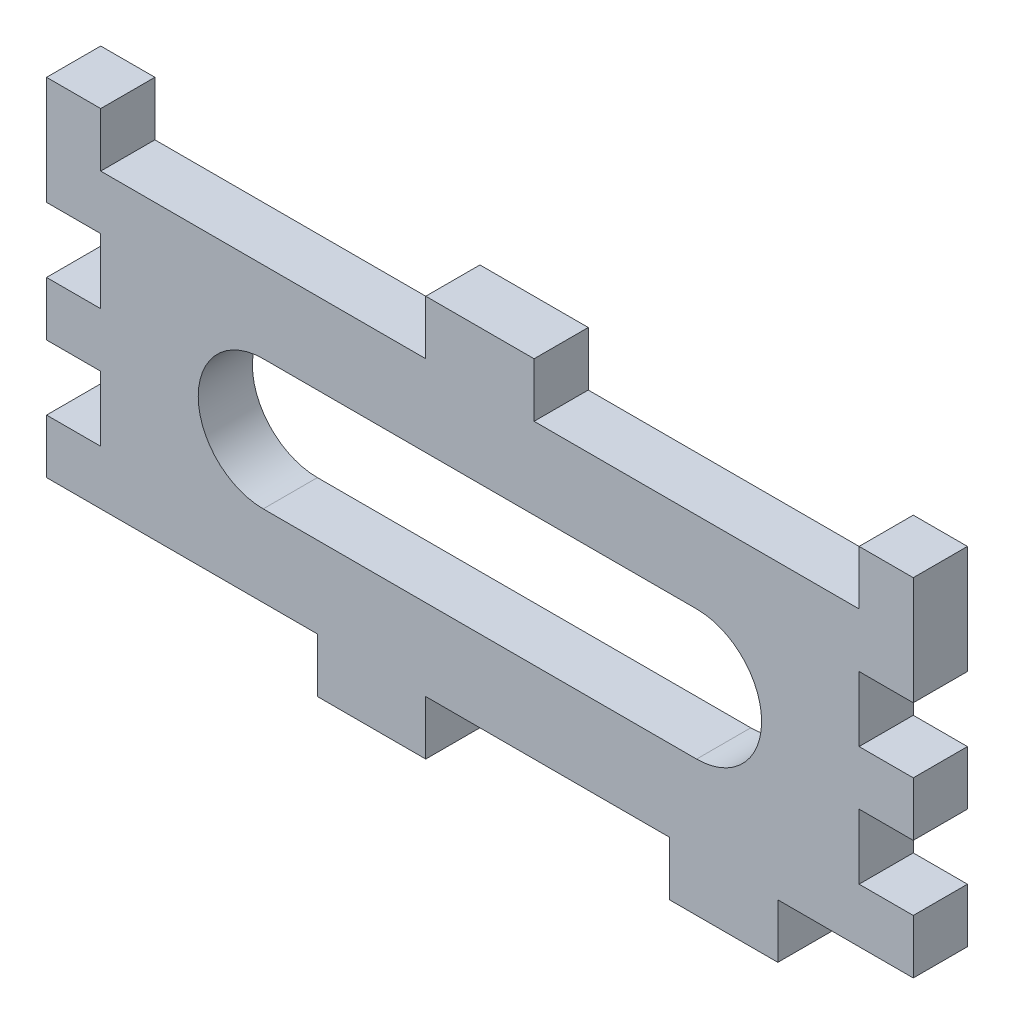
SolidWorks part; units mm, degrees
material "Balsa"
ref_plane "Plan de face" through (0, 0, 0) normal (0, 0, 1) x (1, 0, 0)
ref_plane "Plan de dessus" through (0, 0, 0) normal (0, 1, 0) x (1, 0, 0)
ref_plane "Plan de droite" through (0, 0, 0) normal (1, 0, 0) x (0, 0, -1)
sketch "Esquisse1" plane through (0, 0, 0) normal (0, 0, 1) x (1, 0, 0)
  line L1 (-138.9836, 170.4211) -> (-58.9836, 170.4211)
  line L2 (-138.9836, 170.4211) -> (-138.9836, 143.4211)
  line L3 (-138.9836, 143.4211) -> (-58.9836, 143.4211)
  line L4 (-58.9836, 170.4211) -> (-58.9836, 143.4211)
extrude "Boss.-Extru.1" add sketch "Esquisse1" against normal blind 5
sketch "Esquisse2" plane through (0, 0, 0) normal (0, 0, 1) x (1, 0, 0)
  line L0 (-98.9836, 223.4211) -> (-98.9836, 138.4211) construction
  line L1 (-118.9836, 156.9211) -> (-78.9836, 156.9211) construction
  line L2 (-118.9836, 162.9211) -> (-78.9836, 162.9211)
  line L3 (-118.9836, 150.9211) -> (-78.9836, 150.9211)
  line L4 (-138.9836, 143.4211) -> (-58.9836, 143.4211) construction
  line L5 (-58.9836, 143.4211) -> (-58.9836, 170.4211) construction
  line L6 (-63.9836, 165.4211) -> (-58.9836, 165.4211)
  line L7 (-63.9836, 165.4211) -> (-63.9836, 159.4211)
  line L8 (-63.9836, 159.4211) -> (-58.9836, 159.4211)
  line L9 (-58.9836, 165.4211) -> (-58.9836, 159.4211)
  line L10 (-138.9836, 143.4211) -> (-58.9836, 143.4211) construction
  line L11 (-63.9836, 154.4211) -> (-58.9836, 154.4211)
  line L12 (-63.9836, 154.4211) -> (-63.9836, 148.4211)
  line L13 (-63.9836, 148.4211) -> (-58.9836, 148.4211)
  line L14 (-58.9836, 154.4211) -> (-58.9836, 148.4211)
  line L15 (-58.9836, 170.4211) -> (-138.9836, 170.4211) construction
  line L16 (-138.9836, 154.4211) -> (-138.9836, 148.4211)
  line L17 (-133.9836, 148.4211) -> (-138.9836, 148.4211)
  line L18 (-133.9836, 154.4211) -> (-133.9836, 148.4211)
  line L19 (-133.9836, 154.4211) -> (-138.9836, 154.4211)
  line L20 (-138.9836, 165.4211) -> (-138.9836, 159.4211)
  line L21 (-133.9836, 159.4211) -> (-138.9836, 159.4211)
  line L22 (-133.9836, 165.4211) -> (-133.9836, 159.4211)
  line L23 (-133.9836, 165.4211) -> (-138.9836, 165.4211)
  arc A0 (-118.9836, 162.9211) -> (-118.9836, 150.9211) centre (-118.9836, 156.9211) ccw
  arc A1 (-78.9836, 150.9211) -> (-78.9836, 162.9211) centre (-78.9836, 156.9211) ccw
  point P4 (-98.9836, 156.9211)
  dimension "D2" = 6
  dimension "D1" = 40
  dimension "D3" = 13.5
  dimension "D4" = 35
  dimension "D5" = 6
  dimension "D6" = 6
  dimension "D7" = 5
  dimension "D8" = 5
extrude "Créneaux -" cut sketch "Esquisse2" against normal blind 5
sketch "Esquisse3" plane through (0, 0, 0) normal (0, 0, 1) x (1, 0, 0)
  line L0 (-138.9836, 143.4211) -> (-58.9836, 143.4211) construction
  line L1 (-58.9836, 170.4211) -> (-63.9836, 170.4211)
  line L2 (-58.9836, 170.4211) -> (-58.9836, 175.4211)
  line L3 (-58.9836, 175.4211) -> (-63.9836, 175.4211)
  line L4 (-63.9836, 170.4211) -> (-63.9836, 175.4211)
  line L5 (-71.4836, 143.4211) -> (-81.4836, 143.4211)
  line L6 (-71.4836, 143.4211) -> (-71.4836, 138.4211)
  line L7 (-113.9836, 138.4211) -> (-103.9836, 138.4211)
  line L8 (-81.4836, 143.4211) -> (-81.4836, 138.4211)
  line L9 (-93.9836, 170.4211) -> (-93.9836, 175.4211)
  line L10 (-58.9836, 170.4211) -> (-138.9836, 170.4211) construction
  line L11 (-98.9836, 223.4211) -> (-98.9836, 138.4211) construction
  line L12 (-103.9836, 170.4211) -> (-103.9836, 175.4211)
  line L13 (-103.9836, 143.4211) -> (-103.9836, 138.4211)
  line L15 (-113.9836, 143.4211) -> (-113.9836, 138.4211)
  line L16 (-113.9836, 143.4211) -> (-103.9836, 143.4211)
  line L17 (-133.9836, 170.4211) -> (-133.9836, 175.4211)
  line L18 (-138.9836, 175.4211) -> (-133.9836, 175.4211)
  line L19 (-138.9836, 170.4211) -> (-138.9836, 175.4211)
  line L20 (-138.9836, 170.4211) -> (-133.9836, 170.4211)
  line L21 (-103.9836, 175.4211) -> (-93.9836, 175.4211)
  line L22 (-93.9836, 170.4211) -> (-103.9836, 170.4211)
  line L23 (-58.9836, 165.4211) -> (-58.9836, 170.4211) construction
  line L24 (-81.4836, 138.4211) -> (-71.4836, 138.4211)
  dimension "D1" = 5
  dimension "D2" = 5
  dimension "D3" = 10
  dimension "D5" = 17.5
  dimension "D6" = 10
  dimension "D7" = 5
  dimension "D8" = 10
  dimension "D9" = 5
extrude "Créneaux +" add sketch "Esquisse3" against normal blind 5
